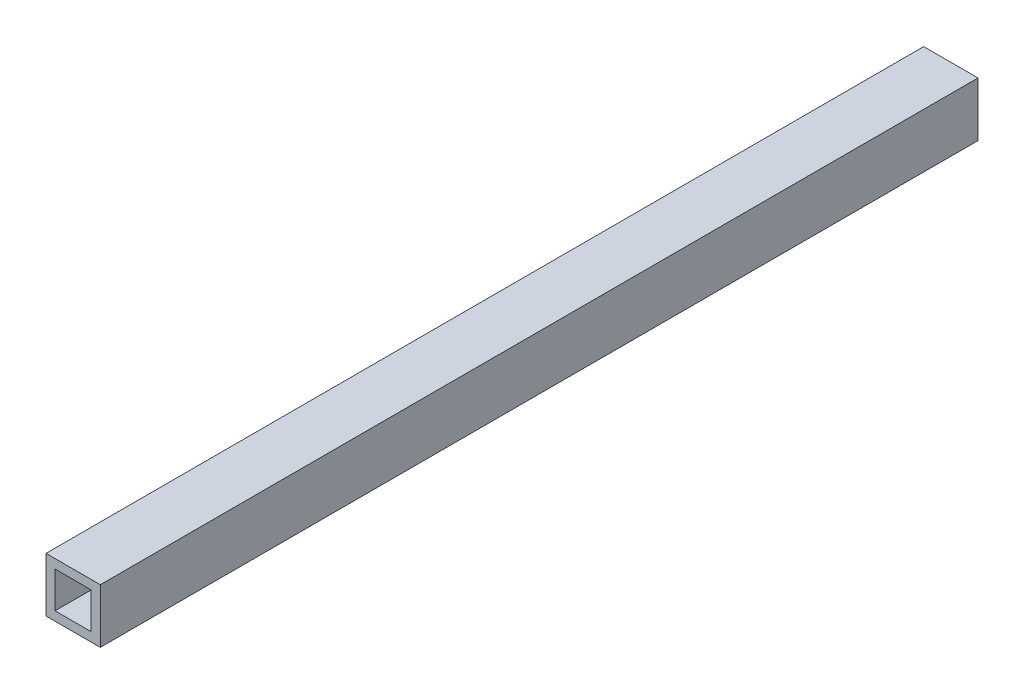
SolidWorks part; units mm, degrees
material "6061-T6 (SS)"
ref_plane "Front Plane" through (0, 0, 0) normal (0, 0, 1) x (1, 0, 0)
ref_plane "Top Plane" through (0, 0, 0) normal (0, 1, 0) x (1, 0, 0)
ref_plane "Right Plane" through (0, 0, 0) normal (1, 0, 0) x (0, 0, -1)
sketch "Sketch1" plane through (0, 0, 0) normal (0, 0, 1) x (1, 0, 0)
  line L1 (-9.525, -9.525) -> (9.525, -9.525)
  line L2 (-9.525, -9.525) -> (-9.525, 9.525)
  line L3 (-9.525, 9.525) -> (9.525, 9.525)
  line L4 (9.525, -9.525) -> (9.525, 9.525)
  line L5 (-9.525, -9.525) -> (9.525, 9.525) construction
  line L6 (-9.525, 9.525) -> (9.525, -9.525) construction
  line L7 (-6.35, -6.35) -> (6.35, -6.35)
  line L8 (-6.35, -6.35) -> (-6.35, 6.35)
  line L9 (-6.35, 6.35) -> (6.35, 6.35)
  line L10 (6.35, -6.35) -> (6.35, 6.35)
  line L11 (-6.35, -6.35) -> (6.35, 6.35) construction
  line L12 (-6.35, 6.35) -> (6.35, -6.35) construction
  point P0 (0, 0)
  point P5 (0, 0)
  dimension "D1" = 19.05
  dimension "D2" = 3.175
extrude "Boss-Extrude1" add sketch "Sketch1" along normal mid plane 307.975
